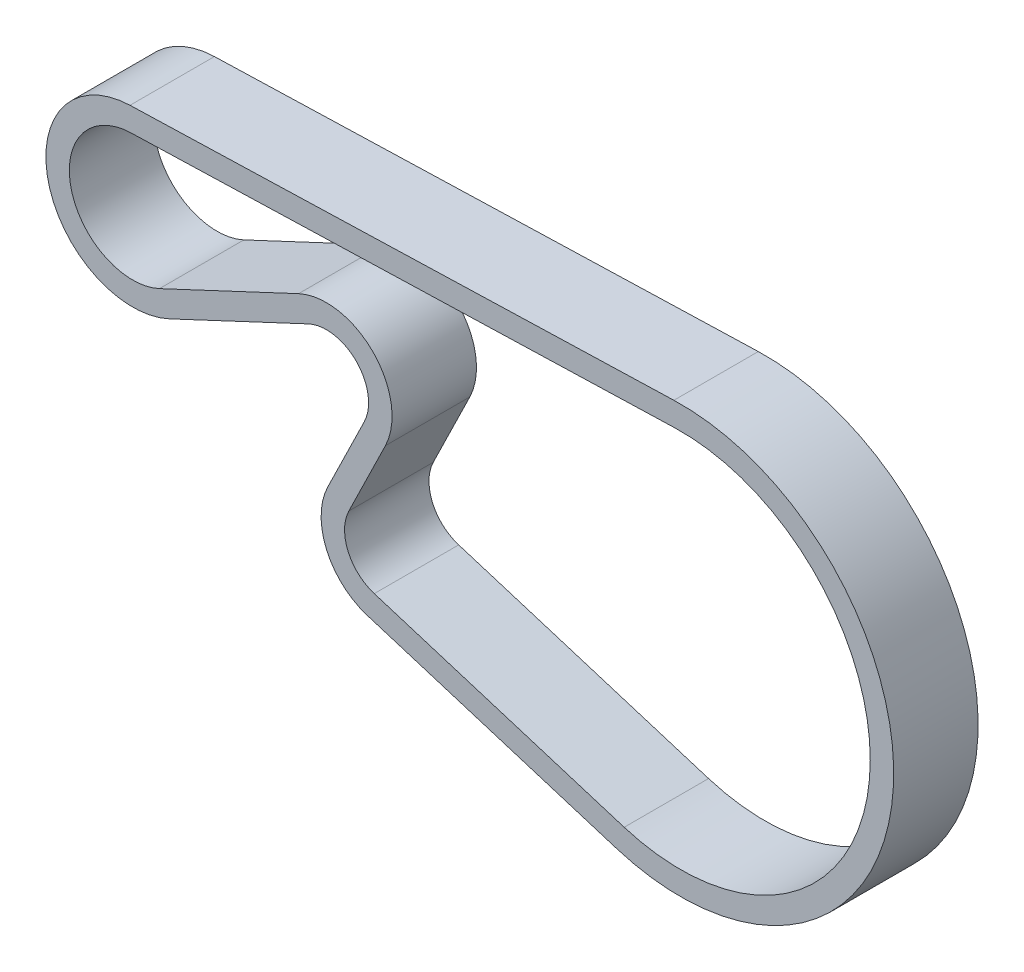
SolidWorks part; units mm, degrees
material "Beryllium"
ref_plane "Front Plane" through (0, 0, 0) normal (0, 0, 1) x (1, 0, 0)
ref_plane "Top Plane" through (0, 0, 0) normal (0, 1, 0) x (1, 0, 0)
ref_plane "Right Plane" through (0, 0, 0) normal (1, 0, 0) x (0, 0, -1)
sketch "Sketch1" plane through (0, 0, 0) normal (0, 0, 1) x (1, 0, 0)
  line L0 (72.976, -52.1087) -> (13.6583, -79.906)
  line L1 (87.8092, -114.9464) -> (103.4013, -83.0315)
  line L2 (101.6703, -147.0131) -> (208.2621, -180.0257)
  line L3 (231.1002, -11.9149) -> (-0.8897, -18.9445)
  line L5 (108.4748, -125.0426) -> (0.0795, -50.9298) construction
  arc A0 (87.8092, -114.9464) -> (101.6703, -147.0131) centre (108.4748, -125.0426) ccw
  arc A1 (208.2621, -180.0257) -> (231.1002, -11.9149) centre (233.7049, -97.8755) ccw
  arc A2 (178.671, -161.3362) -> (214.4372, -179.6358) centre (233.7049, -97.8755) ccw construction
  circle A3 centre (108.4748, -125.0426) radius 11.9255 construction
  circle A5 centre (0.0795, -50.9298) radius 20.75 construction
  circle A6 centre (82.7357, -72.9353) radius 5.0554 construction
  arc A9 (-0.8897, -18.9445) -> (13.6583, -79.906) centre (0.0795, -50.9298) ccw
  arc A10 (103.4013, -83.0315) -> (72.976, -52.1087) centre (82.7357, -72.9353) ccw
  point P7 (79.0846, 51.2318)
  point P10 (-27.8987, -2.393)
  dimension "D1" = 23
  dimension "D4" = 86
  dimension "D3" = 32
extrude "Extrude-Thin1" add sketch "Sketch1" along normal blind 28 and the other way blind 8 thin thin type mid plane wall 10
